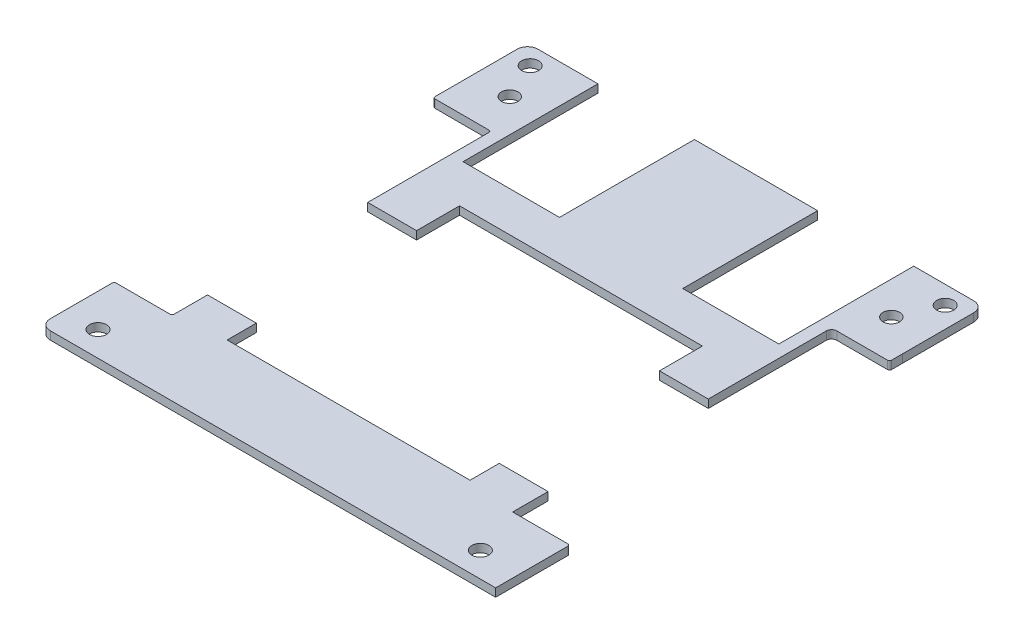
SolidWorks part; units mm, degrees
material "Copper"
ref_plane "Front Plane" through (0, 0, 0) normal (0, 0, 1) x (1, 0, 0)
ref_plane "Top Plane" through (0, 0, 0) normal (0, 1, 0) x (1, 0, 0)
ref_plane "Right Plane" through (0, 0, 0) normal (1, 0, 0) x (0, 0, -1)
sketch "Sketch1" plane through (0, 0, 0) normal (0, 1, 0) x (1, 0, 0)
  line L0 (-44, 45) -> (-44, 29.1624)
  line L1 (-43.6121, 28.7745) -> (-33.2119, 28.7745)
  line L2 (-42, 47) -> (42, 47)
  line L3 (44, 45) -> (44, 31.284)
  line L4 (32.8228, 27.7745) -> (32.8228, -30.4694)
  line L5 (26.2188, 17.9319) -> (-33.6927, 17.9319) construction
  line L6 (33.8228, 28.7745) -> (43.6111, 28.7745)
  line L7 (43.8497, -38.27) -> (43.8497, -47)
  line L8 (42.7059, -47) -> (-42, -47)
  line L9 (-44, -45) -> (-44, -38.977)
  line L10 (-32.824, 28.3866) -> (-32.824, -32.3056)
  line L11 (33.824, -32.6935) -> (36.0988, -32.6935)
  line L12 (23.409, -31.5) -> (-23.409, -31.5)
  line L13 (-23.409, -31.5) -> (-23.409, 13.2954)
  line L14 (-23.409, 13.2954) -> (-12.909, 13.2954)
  line L15 (-12.909, 13.2954) -> (-12.909, 25.9954)
  line L16 (-12.909, 25.9954) -> (12.909, 25.9954)
  line L17 (12.909, 25.9954) -> (12.909, 13.2954)
  line L18 (12.909, 13.2954) -> (23.409, 13.2954)
  line L19 (23.409, 13.2954) -> (23.409, -31.5)
  line L20 (43.8497, -38.27) -> (43.8497, -33.0814)
  line L21 (43.4618, -32.6935) -> (36.0988, -32.6935)
  line L22 (43.8497, -47) -> (42.7059, -47)
  line L23 (-44, 28.7745) -> (52.9697, 28.7745) construction
  line L24 (44, 31.284) -> (43.999, 29.1622)
  line L25 (-33.2119, -32.6935) -> (-36.1, -32.6935)
  line L26 (-44, -38.977) -> (-44, -33.0814)
  line L27 (-43.6121, -32.6935) -> (-36.1, -32.6935)
  line L28 (32.8228, -30.4694) -> (32.8228, -32.6935)
  line L29 (32.8228, -32.6935) -> (33.824, -32.6935)
  circle A0 centre (40, 43.5) radius 1.6383
  circle A1 centre (-40, 43.5) radius 1.6383
  circle A2 centre (-37.6, -42.2) radius 1.6383
  circle A3 centre (36.1, -42.2) radius 1.6383
  arc A5 (-42, 47) -> (-44, 45) centre (-42, 45) ccw
  arc A6 (44, 45) -> (42, 47) centre (42, 45) ccw
  arc A7 (-32.824, -32.3056) -> (-33.2119, -32.6935) centre (-33.2119, -32.3056) cw
  arc A10 (-33.2119, 28.7745) -> (-32.824, 28.3866) centre (-33.2119, 28.3866) cw
  arc A11 (-44, -45) -> (-42, -47) centre (-42, -45) ccw
  arc A12 (-44, 29.1624) -> (-43.6121, 28.7745) centre (-43.6121, 29.1624) ccw
  arc A13 (43.999, 29.1622) -> (43.6111, 28.7745) centre (43.6111, 29.1624) cw
  arc A14 (43.8497, -33.0814) -> (43.4618, -32.6935) centre (43.4618, -33.0814) ccw
  arc A15 (-44, -33.0814) -> (-43.6121, -32.6935) centre (-43.6121, -33.0814) cw
  arc A16 (33.8228, 28.7745) -> (32.8228, 27.7745) centre (33.8228, 27.7745) ccw
  point P27 (32.8228, -32.6935)
  point P51 (-32.824, -32.6935)
  point P54 (-32.824, 28.7745)
  point P60 (43.9988, 28.7745)
  point P67 (32.8228, 28.7745)
  dimension "D24" = 61.468
  dimension "D3" = 80
  dimension "D8" = 3.2766
  dimension "D22" = 1
  dimension "D2" = 6.4
  dimension "D4" = 44.7954
  dimension "D5" = 12.7
  dimension "D6" = 44.7954
  dimension "D7" = 3.5
  dimension "D9" = 4
  dimension "D10" = 3.5
  dimension "D11" = 85.7
  dimension "D12" = 85.7
  dimension "D13" = 21.0046
  dimension "D14" = 11.176
  dimension "D15" = 84
  dimension "D16" = 25.818
  dimension "D17" = 12.7
  dimension "D18" = 46.818
  dimension "D19" = 10.5
  dimension "D20" = 10.5
  dimension "D21" = 73.7
  dimension "D23" = 13.716
  dimension "D26" = 6.604
  dimension "D29" = 11.176
  dimension "D30" = 61.468
  dimension "D31" = 3.276
  dimension "D32" = 3.276
extrude "Boss-Extrude1" add sketch "Sketch1" along normal blind 1.575
sketch "Sketch2" plane through (0, 1.575, 0) normal (0, 1, 0) x (1, 0, 0)
  line L0 (-12.909, 19.06) -> (-30.435, 19.06)
  line L1 (42, 47) -> (-42, 47) construction
  line L2 (-12.909, 25.9954) -> (12.909, 25.9954) construction
  line L3 (-30.435, 47) -> (30.435, 47)
  line L4 (12.909, 13.2954) -> (12.909, 25.9954) construction
  line L5 (12.909, 19.06) -> (30.435, 19.06)
  line L6 (30.435, 19.06) -> (30.435, 47)
  line L7 (0, 47) -> (0, -47) construction
  line L8 (-42, -47) -> (43.8497, -47) construction
  line L9 (-12.909, 25.9954) -> (-12.909, 19.06)
  line L10 (-30.435, 19.06) -> (-30.435, 47)
  line L11 (12.909, 25.9954) -> (12.909, 19.06)
  line L13 (-12.909, 25.9954) -> (12.909, 25.9954)
  dimension "D1" = 27.94
  dimension "D2" = 17.526
extrude "Cut-Extrude1" cut sketch "Sketch2" against normal blind 2.54
sketch "Sketch15" plane through (0, 1.575, 0) normal (0, 1, 0) x (1, 0, 0)
  line L0 (-30.435, 47) -> (-30.435, 19.06) construction
  line L4 (42, 47) -> (30.435, 47) construction
  line L5 (30.435, 19.06) -> (30.435, 47) construction
  circle A0 centre (-36.785, 36.35) radius 1.6
  circle A1 centre (36.785, 36.332) radius 1.6
  dimension "D1" = 3.2
  dimension "D3" = 3.2
  dimension "D4" = 10.668
  dimension "D2" = 6.35
  dimension "D5" = 6.35
extrude "Cut-Extrude5" cut sketch "Sketch15" against normal through all
sketch "Sketch16" plane through (0, 1.575, 0) normal (0, 1, 0) x (1, 0, 0)
  line L0 (-42, 47) -> (42, 47) construction
  line L1 (12.909, 19.06) -> (12.909, 13.2954)
  line L2 (12.909, 13.2954) -> (-12.909, 13.2954)
  line L3 (-11.8389, 47) -> (-11.8389, 21)
  line L4 (-30.435, 21) -> (-11.8389, 21)
  line L5 (11.909, 21) -> (11.909, 47)
  line L6 (11.909, 47) -> (-11.8389, 47)
  line L7 (-30.435, 47) -> (-30.435, 19.06) construction
  line L9 (-12.909, 19.06) -> (-12.909, 13.2954)
  line L10 (-30.435, 47) -> (-42, 47) construction
  line L11 (11.909, 21) -> (30.435, 21)
  line L12 (30.435, 19.06) -> (30.435, 47) construction
  line L13 (30.435, 21) -> (30.435, 19.06)
  line L14 (30.435, 19.06) -> (12.909, 19.06)
  line L15 (-30.435, 21) -> (-30.435, 19.06)
  line L16 (-30.435, 19.06) -> (-12.909, 19.06)
  dimension "D1" = 26
extrude "Boss-Extrude2" add sketch "Sketch16" against normal blind 1.575
sketch "Sketch17" plane through (0, 1.575, 0) normal (0, 1, 0) x (1, 0, 0)
  line L2 (-42.6204, -10.5244) -> (-42.6204, -23.1918)
  line L3 (-42.6204, -23.1918) -> (43.1801, -23.1918)
  line L4 (43.1801, -10.5244) -> (43.1801, -23.1918)
  line L6 (-42.6204, -10.5244) -> (-42.6204, 5.0143)
  line L7 (-42.6204, 5.0143) -> (43.1801, 5.0143)
  line L8 (43.1801, -10.5244) -> (43.1801, 5.0143)
extrude "Cut-Extrude7" cut sketch "Sketch17" against normal through all
sketch "Sketch18" plane through (0, 1.575, 0) normal (0, 1, 0) x (1, 0, 0)
  line L1 (33.4307, -29.0671) -> (45.3514, -29.0671)
  line L2 (33.4307, -29.0671) -> (33.4307, -32.653)
  line L3 (33.4307, -32.653) -> (45.3514, -32.653)
  line L4 (45.3514, -29.0671) -> (45.3514, -32.653)
  dimension "D1" = 14.347
  dimension "D2" = 10.419
sketch "Sketch21" plane through (0, 1.575, 0) normal (0, 1, 0) x (1, 0, 0)
  line L0 (-32.824, 28.3866) -> (-32.824, -32.3056) construction
  line L1 (-32.824, -23.1918) -> (32.8228, -23.1918)
  line L2 (-32.824, -23.1918) -> (-32.824, -25.8658)
  line L3 (-32.824, -25.8658) -> (32.8228, -25.8658)
  line L4 (32.8228, -23.1918) -> (32.8228, -25.8658)
  dimension "D1" = 2.674
extrude "Cut-Extrude10" cut sketch "Sketch21" against normal through all
sketch "Sketch20" plane through (0, 1.575, 0) normal (0, 1, 0) x (1, 0, 0)
